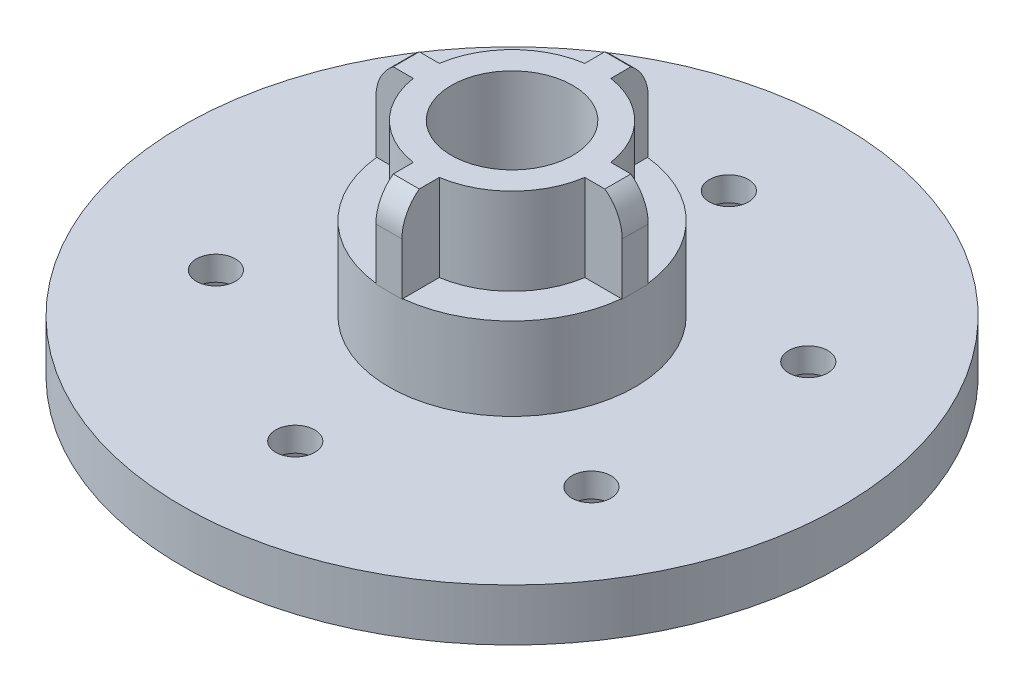
SolidWorks part; units mm, degrees
ref_plane "Front Plane" through (0, 0, 0) normal (0, 0, 1) x (1, 0, 0)
ref_plane "Top Plane" through (0, 0, 0) normal (0, 1, 0) x (1, 0, 0)
ref_plane "Right Plane" through (0, 0, 0) normal (1, 0, 0) x (0, 0, -1)
sketch "Sketch2" plane through (0, 0, 0) normal (0, 0, 1) x (1, 0, 0)
  line L0 (0, 0) -> (0, 64.2848) construction
  line L2 (7, 25.525) -> (10, 25.525)
  line L3 (14.2, 15.525) -> (14.2, 6)
  line L4 (14.2, 6) -> (38, 6)
  line L5 (38, 6) -> (38, 0)
  line L6 (38, 0) -> (11.2, 0)
  line L7 (11.2, 0) -> (11.2, 7)
  line L8 (11.2, 7) -> (7, 7)
  line L9 (7, 7) -> (7, 25.525)
  line L10 (10, 25.525) -> (10, 15.525)
  line L11 (10, 15.525) -> (14.2, 15.525)
  dimension "D1" = 22.4
  dimension "D2" = 7
  dimension "D3" = 3
  dimension "D6" = 14
  dimension "D8" = 6
  dimension "D9" = 76
  dimension "D7" = 10
  dimension "D4" = 9.525
  dimension "D10" = 20
revolve "Revolve1" add sketch "Sketch2" angle 360 about L0
sketch "Sketch4" plane through (0, 0, 0) normal (0, 0, 1) x (1, 0, 0)
  line L0 (-7, 25.525) -> (-12.2, 25.525)
  line L2 (-14.2, 21.525) -> (-14.2, 15.525)
  line L3 (-14.2, 15.525) -> (-7, 15.525)
  line L4 (14.2, 15.525) -> (-14.2, 15.525) construction
  line L5 (-7, 15.525) -> (-7, 25.525)
  line L6 (10, 25.525) -> (-10, 25.525) construction
  arc A0 (-12.2, 25.525) -> (-14.2, 21.525) centre (-9.2, 21.525) ccw
  dimension "D2" = 2
  dimension "D3" = 4
extrude "Boss-Extrude1" add sketch "Sketch4" along normal mid plane 3
pattern_circular "CirPattern1" count 4 over 360 about axis through (0, 0, 0) along (0, 1, 0) of "Boss-Extrude1"
sketch "Sketch5" plane through (0, 6, 0) normal (0, 1, 0) x (1, 0, 0)
  circle A0 centre (0, 25) radius 2.25
  dimension "D1" = 4.5
  dimension "D2" = 25
extrude "Cut-Extrude1" cut sketch "Sketch5" against normal through all
sketch "Sketch6" plane through (0, 0, 0) normal (0, -1, 0) x (1, 0, 0)
  line L1 (4.1569, -25) -> (2.0785, -21.4)
  line L2 (2.0785, -21.4) -> (-2.0785, -21.4)
  line L3 (-2.0785, -21.4) -> (-4.1569, -25)
  line L4 (-4.1569, -25) -> (-2.0785, -28.6)
  line L5 (-2.0785, -28.6) -> (2.0785, -28.6)
  line L6 (2.0785, -28.6) -> (4.1569, -25)
  circle A0 centre (0, -25) radius 3.6 construction
  dimension "D1" = 7.2
extrude "Cut-Extrude2" cut sketch "Sketch6" against normal blind 3.2
pattern_circular "CirPattern2" count 6 over 360 about axis through (0, 0, 0) along (0, 1, 0) of "Cut-Extrude1", "Cut-Extrude2"
equation "\"D6@Sketch2\"=\"D10@Sketch2\"-6"
